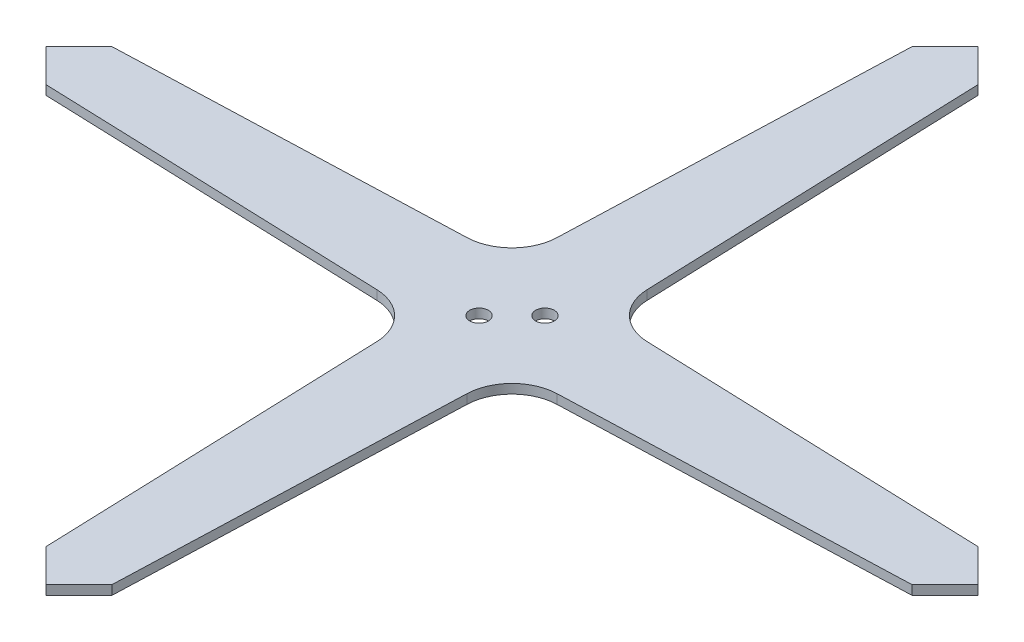
SolidWorks part; units mm, degrees
ref_plane "Front Plane" through (0, 0, 0) normal (0, 0, 1) x (1, 0, 0)
ref_plane "Top Plane" through (0, 0, 0) normal (0, 1, 0) x (1, 0, 0)
ref_plane "Right Plane" through (0, 0, 0) normal (1, 0, 0) x (0, 0, -1)
sketch "Sketch1" plane through (0, 0, 0) normal (0, 1, 0) x (1, 0, 0)
  line L0 (-286.26, 15) -> (-410.6534, 10.6066)
  line L1 (-410.6534, -10.6066) -> (-421.26, 0)
  line L2 (-410.6534, -10.6066) -> (-286.26, -15)
  line L3 (-256.26, 15) -> (-260.6534, 139.3934)
  line L4 (-281.8666, 139.3934) -> (-271.26, 150)
  line L5 (-281.8666, 139.3934) -> (-286.26, 15)
  line L6 (-271.26, 150) -> (-260.6534, 139.3934)
  line L7 (-256.26, -15) -> (-131.8666, -10.6066)
  line L8 (-131.8666, 10.6066) -> (-121.26, 0)
  line L9 (-131.8666, 10.6066) -> (-256.26, 15)
  line L10 (-121.26, 0) -> (-131.8666, -10.6066)
  line L11 (-286.26, -15) -> (-281.8666, -139.3934)
  line L12 (-260.6534, -139.3934) -> (-271.26, -150)
  line L13 (-260.6534, -139.3934) -> (-256.26, -15)
  line L14 (-271.26, -150) -> (-281.8666, -139.3934)
  line L15 (-421.26, 0) -> (-410.6534, 10.6066)
  line L16 (-121.26, 0) -> (-421.26, 0) construction
  line L17 (-271.26, -150) -> (-271.26, 150) construction
  line L18 (-286.26, -15) -> (-256.26, 15) construction
  circle A0 centre (-276.5633, -5.3033) radius 3
  circle A1 centre (-265.9567, 5.3033) radius 3
  point P24 (-271.26, 0)
  dimension "D9" = 15
  dimension "D1" = 6
  dimension "D2" = 6
  dimension "D3" = 90
  dimension "D4" = 15
  dimension "D5" = 15
  dimension "D6" = 7.5
  dimension "D7" = 7.5
  dimension "D10" = 15
  dimension "D11" = 150
  dimension "D8" = 4
extrude "Boss-Extrude1" add sketch "Sketch1" along normal blind 3
fillet "Fillet1" radius 15 4 edges at (-256.26, 1.5, -15) (-286.26, 1.5, -15) (-286.26, 1.5, 15) (-256.26, 1.5, 15)
